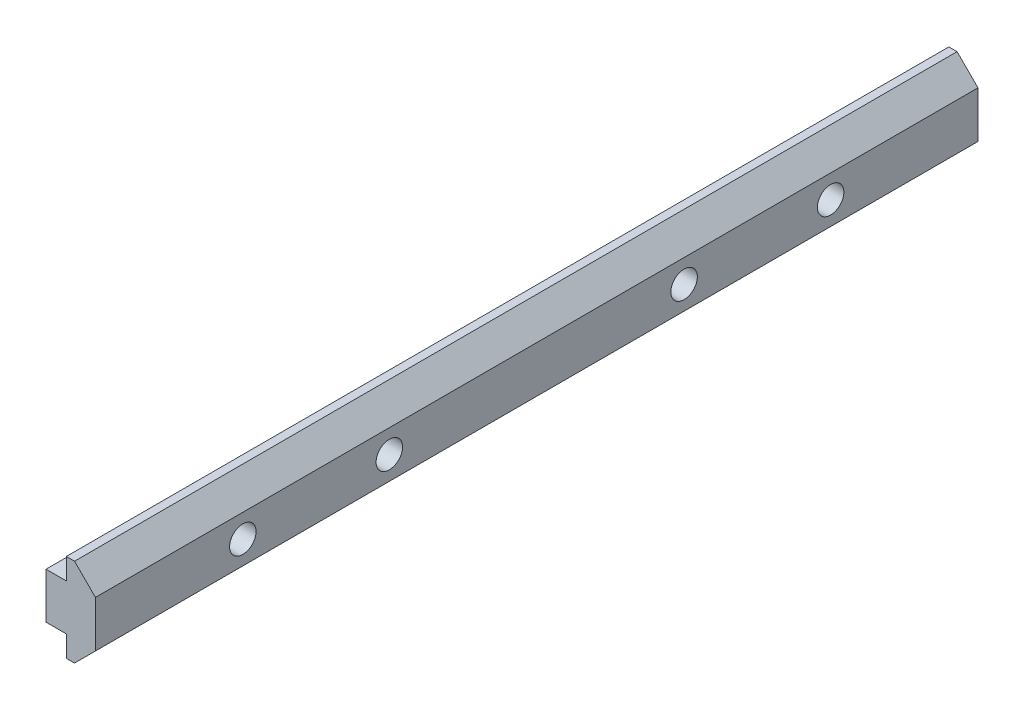
SolidWorks part; units mm, degrees
ref_plane "Front Plane" through (0, 0, 0) normal (0, 0, 1) x (1, 0, 0)
ref_plane "Top Plane" through (0, 0, 0) normal (0, 1, 0) x (1, 0, 0)
ref_plane "Right Plane" through (0, 0, 0) normal (1, 0, 0) x (0, 0, -1)
sketch "Sketch1" plane through (0, 0, 0) normal (0, 0, 1) x (1, 0, 0)
  line L0 (-10, 2.6) -> (-7.7, 2.6)
  line L1 (-7.7, 2.6) -> (-7.7, 5)
  line L2 (-7.7, 5) -> (-6.7678, 5)
  line L3 (-6.7678, 5) -> (-4.4, 2.6322)
  line L4 (-4.4, 2.6322) -> (-4.4, -2.6322)
  line L5 (-4.4, -2.6322) -> (-6.7678, -5)
  line L6 (-6.7678, -5) -> (-7.7, -5)
  line L7 (-7.7, -5) -> (-7.7, -2.6)
  line L8 (-7.7, -2.6) -> (-10, -2.6)
  line L9 (-10, -2.6) -> (-10, 2.6)
  line L10 (-10, 8.5) -> (-10, 3.8) construction
  line L11 (-8.2, 5.3) -> (-8.2, 3.1) construction
  line L12 (-8.2, -5.3) -> (-8.2, -3.1) construction
  line L13 (-3.9, 2.7565) -> (-3.9, -2.7565) construction
  line L14 (-3.9586, 2.8979) -> (-6.5607, 5.5) construction
  line L15 (-3.9586, -2.8979) -> (-6.5607, -5.5) construction
  line L16 (-6.5607, -5.5) -> (-8, -5.5) construction
  line L17 (-6.5607, 5.5) -> (-8, 5.5) construction
  line L19 (-8.2, -3.1) -> (-9.3, -3.1) construction
  line L20 (-8.2, 3.1) -> (-9.3, 3.1) construction
  dimension "D1" = 0
  dimension "D2" = 0.5
  dimension "D3" = 0.5
  dimension "D4" = 0.5
  dimension "D5" = 0.5
  dimension "D6" = 0.5
  dimension "D7" = 0.5
  dimension "D8" = 0.5
  dimension "D9" = 0.5
  dimension "D10" = 0.5
extrude "Boss-Extrude1" add sketch "Sketch1" along normal blind 100
sketch "Sketch2" plane through (-10, 0, 0) normal (-1, 0, 0) x (0, 0, 1)
  line L0 (100, 2.6) -> (100, -2.6) construction
  line L1 (50, 2.6) -> (50, -2.6) construction
  line L2 (100, 2.6) -> (0, 2.6) construction
  line L3 (100, -2.6) -> (0, -2.6) construction
  circle A0 centre (83.3, 0) radius 1.5
  circle A2 centre (66.7, 0) radius 1.5
  circle A3 centre (16.7, 0) radius 1.5
  circle A4 centre (33.3, 0) radius 1.5
  point P5 (100, 0)
  dimension "D1" = 16.7
  dimension "D2" = 3
  dimension "D3" = 0
  dimension "D4" = 0
  dimension "D5" = 16.7
  dimension "D6" = 3
extrude "Cut-Extrude1" cut sketch "Sketch2" against normal blind 20
